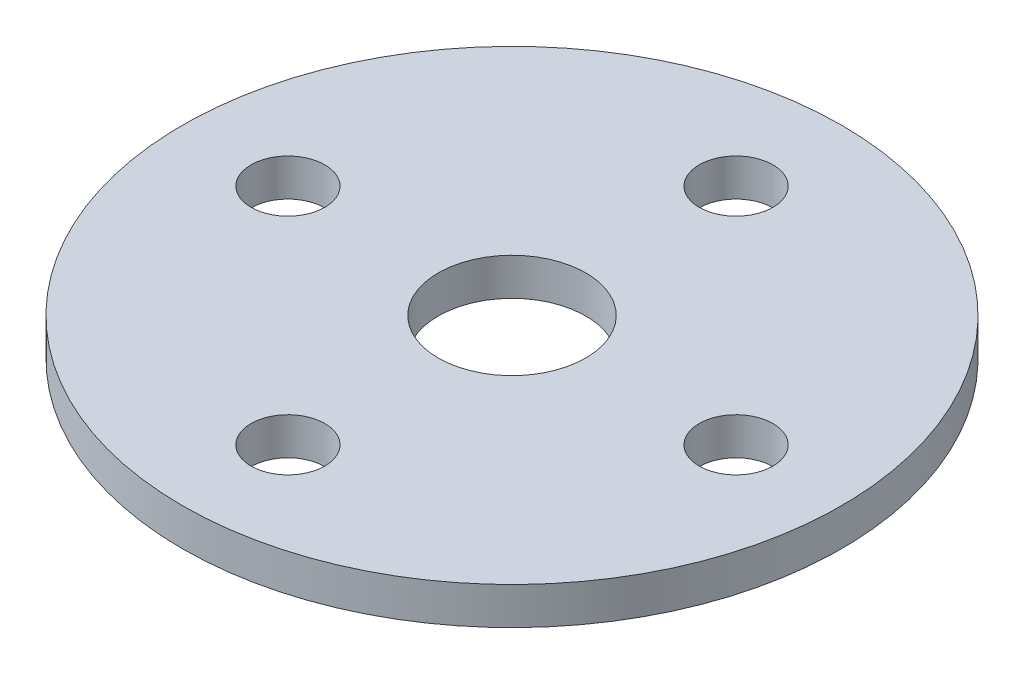
SolidWorks part; units mm, degrees
ref_plane "Front Plane" through (0, 0, 0) normal (0, 0, 1) x (1, 0, 0)
ref_plane "Top Plane" through (0, 0, 0) normal (0, 1, 0) x (1, 0, 0)
ref_plane "Right Plane" through (0, 0, 0) normal (1, 0, 0) x (0, 0, -1)
sketch "Sketch1" plane through (0, 0, 0) normal (0, 1, 0) x (1, 0, 0)
  line L0 (0, 17.65) -> (0, -17.65) construction
  line L1 (-17.65, 0) -> (17.65, 0) construction
  circle A0 centre (0, 0) radius 17.65
  circle A1 centre (0, 0) radius 3.95
  circle A2 centre (0, 12) radius 1.975
  circle A3 centre (-12, 0) radius 1.975
  circle A4 centre (12, 0) radius 1.975
  circle A5 centre (0, -12) radius 1.975
  dimension "D1" = 35.3
  dimension "D2" = 7.9
  dimension "D4" = 3.95
  dimension "D3" = 12
  dimension "D5" = 12
extrude "Boss-Extrude1" add sketch "Sketch1" along normal blind 2
